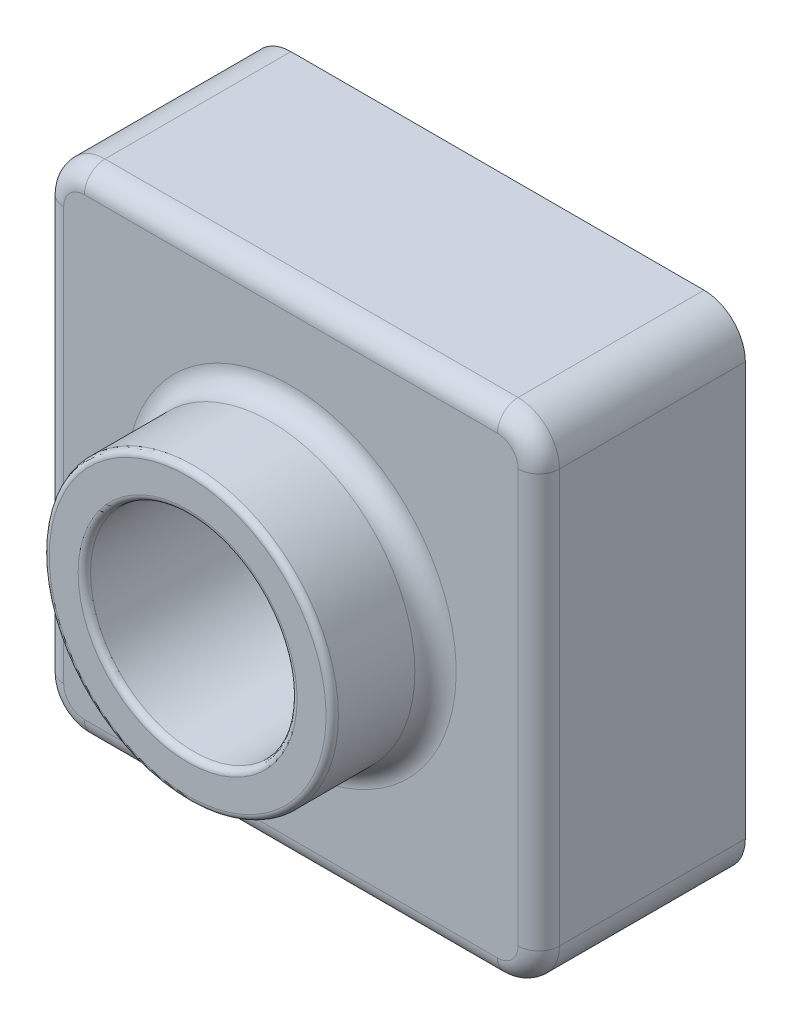
SolidWorks part; units mm, degrees
ref_plane "Front Plane" through (0, 0, 0) normal (0, 0, 1) x (1, 0, 0)
ref_plane "Top Plane" through (0, 0, 0) normal (0, 1, 0) x (1, 0, 0)
ref_plane "Right Plane" through (0, 0, 0) normal (1, 0, 0) x (0, 0, -1)
sketch "Sketch1" plane through (0, 0, 0) normal (0, 0, 1) x (1, 0, 0)
  line L1 (0, 0) -> (120, 0)
  line L2 (0, 0) -> (0, 120)
  line L3 (0, 120) -> (120, 120)
  line L4 (120, 0) -> (120, 120)
  dimension "D1" = 120
  dimension "D2" = 120
extrude "box" add sketch "Sketch1" along normal blind 50
sketch "Sketch2" plane through (0, 0, 0) normal (0, 0, -1) x (-1, 0, 0)
  line L0 (-120, 120) -> (0, 120) construction
  line L2 (0, 120) -> (0, 0) construction
  circle A0 centre (-60, 60) radius 35
  dimension "D1" = 70
  dimension "D3" = 60
  dimension "D2" = 60
extrude "cylindrical part" add sketch "Sketch2" along normal blind 25
sketch "Sketch3" plane through (0, 0, -25) normal (0, 0, -1) x (-1, 0, 0)
  circle A0 centre (-60, 60) radius 25
  dimension "D1" = 50
extrude "Cut-Extrude1" cut sketch "Sketch3" against normal through all
fillet "Fillet1" radius 10 4 edges at (0, 0, 25) (120, 0, 25) (120, 120, 25) (0, 120, 25)
fillet "Fillet2" radius 1.5 2 edges at (25, 60, -25) (35, 60, -25)
fillet "Fillet3" radius 5 9 edges at (117.0711, 2.9289, 0) (120, 60, 0) (117.0711, 117.0711, 0) (60, 120, 0) (2.9289, 117.0711, 0) (0, 60, 0) (2.9289, 2.9289, 0) (60, 0, 0) (25, 60, 0)
shell "Shell1" thickness 2
move or copy body "Body-Move/Copy1" bodies to move or copy 103 copy no rotation origin (0, 60, 12.5) rotation axis (1, 0, 0) rotation angle 180
